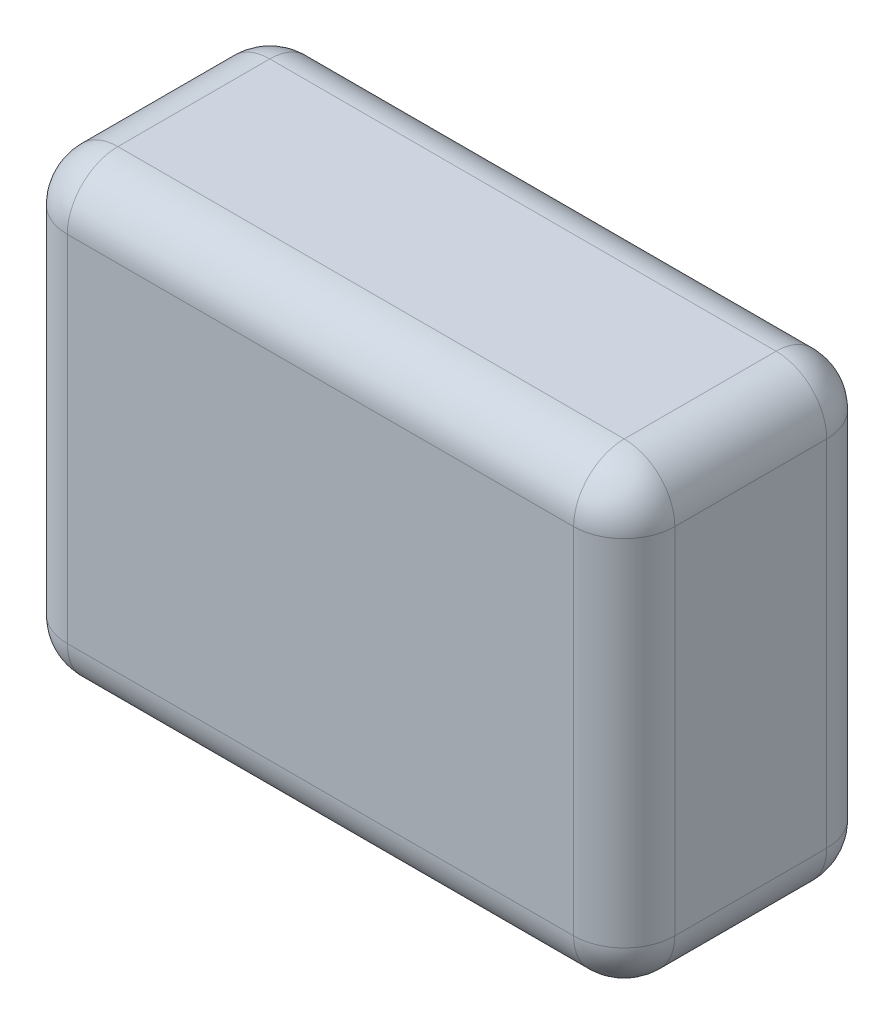
SolidWorks part; units mm, degrees
ref_plane "Front Plane" through (0, 0, 0) normal (0, 0, 1) x (1, 0, 0)
ref_plane "Top Plane" through (0, 0, 0) normal (0, 1, 0) x (1, 0, 0)
ref_plane "Right Plane" through (0, 0, 0) normal (1, 0, 0) x (0, 0, -1)
sketch "Sketch1" plane through (0, 0, 0) normal (0, 0, 1) x (1, 0, 0)
  line L1 (-60, 45) -> (60, 45)
  line L2 (-60, 45) -> (-60, -45)
  line L3 (-60, -45) -> (60, -45)
  line L4 (60, 45) -> (60, -45)
  line L5 (-60, 45) -> (60, -45) construction
  line L6 (-60, -45) -> (60, 45) construction
  point P0 (0, 0)
  dimension "D1" = 120
  dimension "D2" = 90
extrude "Boss-Extrude1" add sketch "Sketch1" along normal blind 50
fillet "Fillet1" radius 10 12 edges at (60, 45, 25) (-60, 45, 25) (-60, -45, 25) (60, -45, 25) (0, -45, 50) (-60, 0, 50) (60, 0, 50) (0, 45, 0) (-60, 0, 0) (0, -45, 0) (60, 0, 0) (0, 45, 50)
